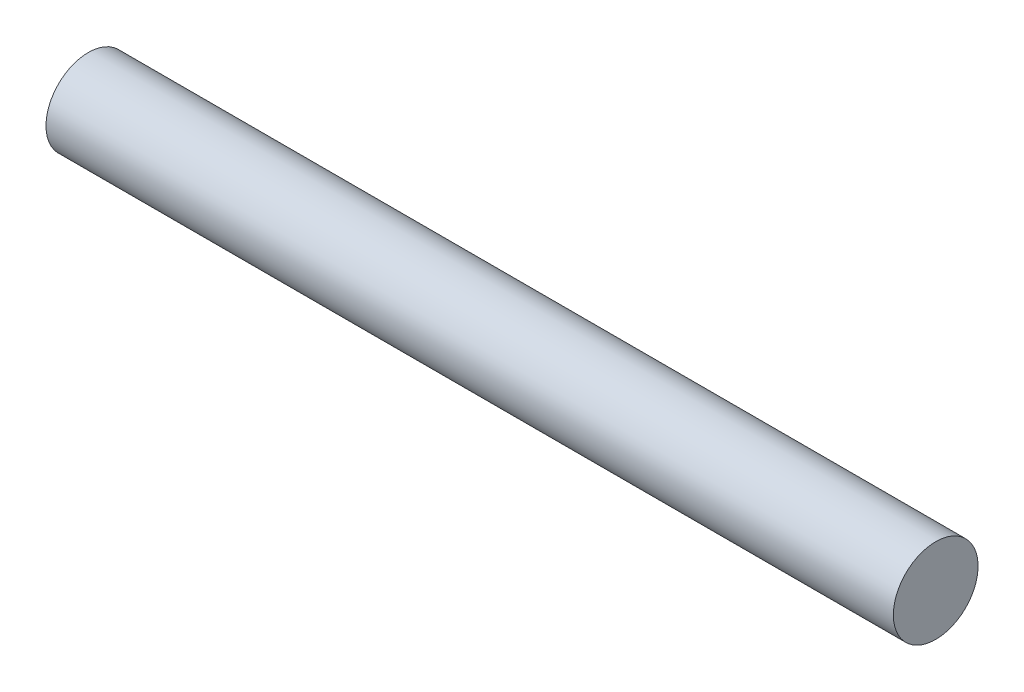
SolidWorks part; units mm, degrees
ref_plane "Front Plane" through (0, 0, 0) normal (0, 0, 1) x (1, 0, 0)
ref_plane "Top Plane" through (0, 0, 0) normal (0, 1, 0) x (1, 0, 0)
ref_plane "Right Plane" through (0, 0, 0) normal (1, 0, 0) x (0, 0, -1)
sketch "Sketch1" plane through (0, 0, 0) normal (0, 0, 1) x (1, 0, 0)
  line L1 (-50, -2.5) -> (50, -2.5)
  line L2 (-50, -2.5) -> (-50, 2.5)
  line L3 (-50, 2.5) -> (50, 2.5)
  line L4 (50, -2.5) -> (50, 2.5)
  line L5 (-50, -2.5) -> (50, 2.5) construction
  line L6 (-50, 2.5) -> (50, -2.5) construction
  point P0 (0, 0)
  dimension "D1" = 100
  dimension "D2" = 5
revolve "Revolve1" add sketch "Sketch1" angle 360 about L1
